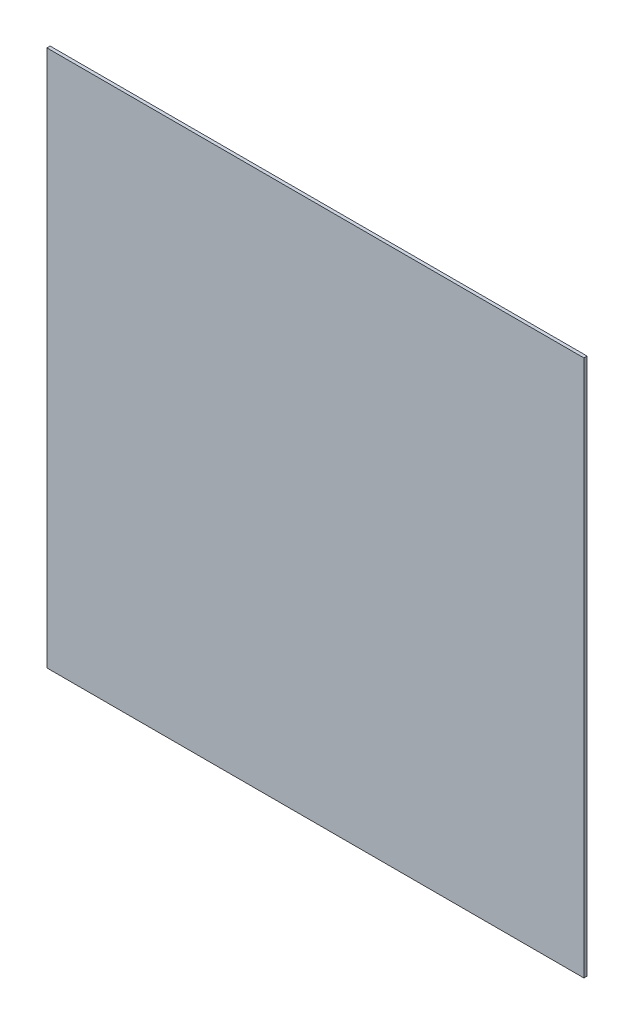
SolidWorks part; units mm, degrees
material "PC Alta Viscosidade"
ref_plane "Plano frontal" through (0, 0, 0) normal (0, 0, 1) x (1, 0, 0)
ref_plane "Plano superior" through (0, 0, 0) normal (0, 1, 0) x (1, 0, 0)
ref_plane "Plano direito" through (0, 0, 0) normal (1, 0, 0) x (0, 0, -1)
sketch "Esboço2" plane through (0, 0, 0) normal (0, 0, 1) x (1, 0, 0)
  line L0 (-250, 0) -> (250, 0) construction
  line L1 (250, -250) -> (-250, -250)
  line L2 (250, -250) -> (250, 250)
  line L3 (250, 250) -> (-250, 250)
  line L4 (-250, -250) -> (-250, 250)
  dimension "D1" = 500
  dimension "D2" = 500
extrude "Ressalto-extrusão1" add sketch "Esboço2" along normal blind 3
